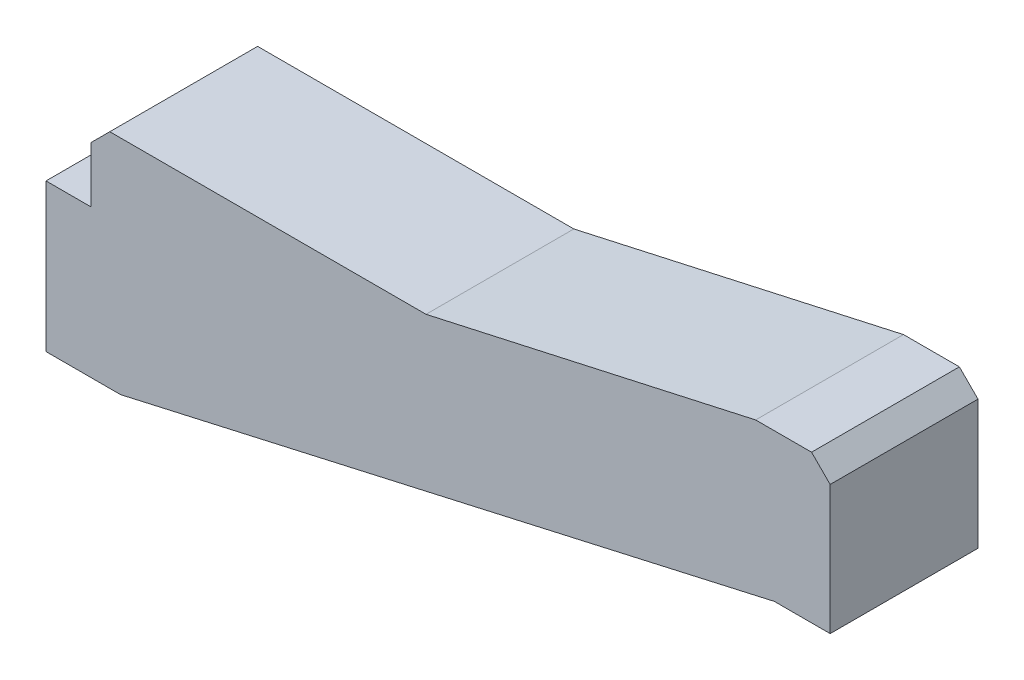
SolidWorks part; units mm, degrees
ref_plane "前基準面" through (0, 0, 0) normal (0, 0, 1) x (1, 0, 0)
ref_plane "上基準面" through (0, 0, 0) normal (0, 1, 0) x (1, 0, 0)
ref_plane "右基準面" through (0, 0, 0) normal (1, 0, 0) x (0, 0, -1)
sketch "Sketch1" plane through (0, 0, 0) normal (0, 0, 1) x (1, 0, 0)
  line L0 (0, 0) -> (1, 0)
  line L1 (1, 0) -> (1, -1.9844)
  line L2 (1, -1.9844) -> (0.25, -1.9844)
  line L3 (0.25, -1.9844) -> (-8.5261, -3.9688)
  line L4 (-8.5261, -3.9688) -> (-9.5261, -3.9688)
  line L5 (-9.5261, -3.9688) -> (-9.5261, -1.9844)
  line L6 (-9.5261, -1.9844) -> (-8.92, -1.9844)
  line L7 (-4.4249, -0.9844) -> (0, 0)
  line L8 (-8.92, -1.9844) -> (-8.92, -0.9844)
  line L9 (-8.92, -0.9844) -> (-4.4249, -0.9844)
  dimension "D1" = 0.75
  dimension "D2" = 1
  dimension "D3" = 1.9844
  dimension "D4" = 1.9844
  dimension "D5" = 9.92
  dimension "D6" = 1.9844
  dimension "D7" = 1
extrude "Boss-Extrude1" add sketch "Sketch1" along normal blind 1.9844
chamfer "Chamfer1" distance 0.25 2 edges at (1, 0, 0.9922) (-8.92, -0.9844, 0.9922)
